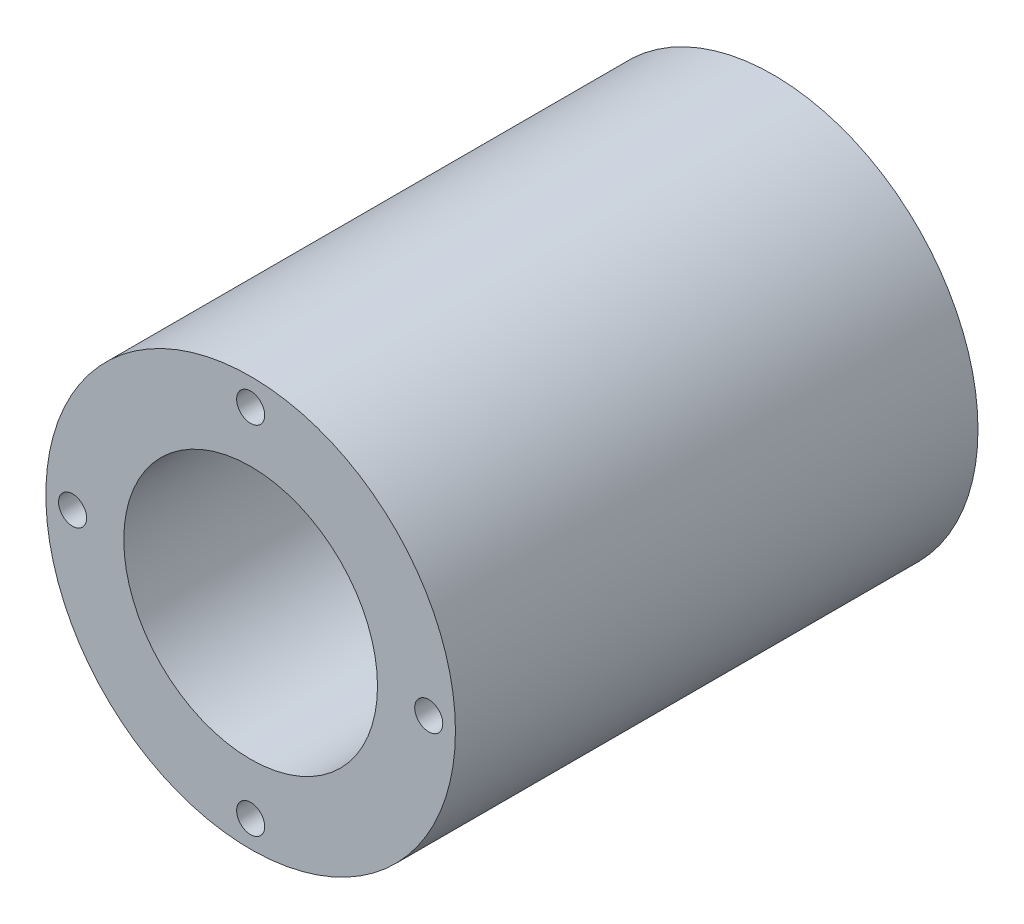
SolidWorks part; units mm, degrees
material "6061-T6 (SS)"
ref_plane "Front Plane" through (0, 0, 0) normal (0, 0, 1) x (1, 0, 0)
ref_plane "Top Plane" through (0, 0, 0) normal (0, 1, 0) x (1, 0, 0)
ref_plane "Right Plane" through (0, 0, 0) normal (1, 0, 0) x (0, 0, -1)
sketch "Sketch Spindle Skeleton" plane through (0, 0, 0) normal (1, 0, 0) x (0, 0, -1)
  line L0 (-95.847, -9.525) -> (-140.95, -9.525)
  line L5 (-1000, 0) -> (49000, 0)
  line L6 (0, -9.525) -> (0, 9.525)
  line L13 (0, 9.525) -> (-45.847, 9.525)
  line L26 (-45.847, 9.525) -> (-45.847, 14)
  line L27 (-45.847, 14) -> (-95.847, 14)
  line L32 (-95.847, 14) -> (-95.847, 9.525)
  line L34 (-160, 7) -> (-160, -7)
  line L36 (-95.847, -9.525) -> (-95.847, -14)
  line L37 (-95.847, -14) -> (-45.847, -14)
  line L38 (-45.847, -14) -> (-45.847, -9.525)
  line L39 (0, -9.525) -> (-45.847, -9.525)
  line L40 (-25.305, 36.5125) -> (-16.305, 36.5125)
  line L41 (-111.341, 22.6187) -> (-95.847, 22.6187)
  line L42 (-111.341, 22.6187) -> (-111.341, -22.6187)
  line L43 (-111.341, -22.6187) -> (-95.847, -22.6187)
  line L44 (-95.847, 22.6187) -> (-95.847, -22.6187)
  line L45 (-111.341, 22.6187) -> (-95.847, -22.6187) construction
  line L46 (-111.341, -22.6187) -> (-95.847, 22.6187) construction
  line L47 (-30.353, 22.6187) -> (-45.847, 22.6187)
  line L48 (-30.353, 22.6187) -> (-30.353, -22.6187)
  line L49 (-30.353, -22.6187) -> (-45.847, -22.6187)
  line L50 (-45.847, 22.6187) -> (-45.847, -22.6187)
  line L51 (-30.353, 22.6187) -> (-45.847, -22.6187) construction
  line L52 (-30.353, -22.6187) -> (-45.847, 22.6187) construction
  line L59 (-16.305, 36.5125) -> (-16.305, -36.5125)
  line L60 (-16.305, -36.5125) -> (-25.305, -36.5125)
  line L61 (-25.305, -22.6187) -> (-27.305, -22.6187)
  line L62 (-27.305, -22.6187) -> (-27.305, -12.5)
  line L63 (-27.305, -12.5) -> (-25.305, -12.5)
  line L64 (-25.305, -12.5) -> (-25.305, 12.5)
  line L65 (-25.305, 12.5) -> (-27.305, 12.5)
  line L66 (-27.305, 12.5) -> (-27.305, 22.6187)
  line L67 (-27.305, 22.6187) -> (-25.305, 22.6187)
  line L68 (-25.305, 22.6187) -> (-25.305, 36.5125)
  line L69 (-25.305, -22.6187) -> (-25.305, -36.5125)
  line L71 (-119.469, 36.5125) -> (-26.305, 36.5125)
  line L72 (-119.469, 36.5125) -> (-119.469, -36.5125)
  line L73 (-119.469, -36.5125) -> (-26.305, -36.5125)
  line L74 (-26.305, 36.5125) -> (-26.305, -36.5125)
  line L75 (-119.469, 36.5125) -> (-26.305, -36.5125) construction
  line L76 (-119.469, -36.5125) -> (-26.305, 36.5125) construction
  line L77 (-140.95, -9.525) -> (-140.95, -7)
  line L78 (-140.95, -7) -> (-160, -7)
  line L79 (-95.847, 9.525) -> (-140.95, 9.525)
  line L80 (-140.95, 7) -> (-160, 7)
  line L81 (-140.95, 9.525) -> (-140.95, 7)
  line L82 (-118.3985, 9.525) -> (-118.3985, -9.525) construction
  line L83 (-22.9235, 9.525) -> (-22.9235, -9.525) construction
  line L96 (-119.469, 36.5125) -> (-134.709, 36.5125)
  line L98 (-119.469, -36.5125) -> (-134.709, -36.5125)
  line L99 (-134.709, 36.5125) -> (-134.709, -36.5125)
  line L110 (-119.469, 36.5125) -> (-119.469, -36.5125)
  point P3 (0, 0)
  point P7 (0, 0)
  point P18 (-103.594, 0)
  point P24 (-38.1, 0)
  point P29 (-72.887, 0)
  point P44 (0, 0)
  point P45 (0, 0)
  point P48 (-16.305, 30.5656)
  point P58 (0, 0)
  point P59 (0, 0)
  point P70 (-134.709, 31.75)
sketch "Sketch1" plane through (0, 0, 0) normal (1, 0, 0) x (0, 0, -1)
  line L0 (-26.305, 36.5125) -> (-26.305, -36.5125) construction
  line L1 (-119.469, -36.5125) -> (-26.305, -36.5125) construction
  line L2 (-119.469, 36.5125) -> (-119.469, -36.5125) construction
  line L3 (-119.469, 36.5125) -> (-26.305, 36.5125) construction
  line L4 (-26.305, 36.5125) -> (-26.305, -36.5125)
  line L5 (-119.469, -36.5125) -> (-26.305, -36.5125)
  line L6 (-119.469, 36.5125) -> (-119.469, -36.5125)
  line L7 (-119.469, 36.5125) -> (-26.305, 36.5125)
  line L9 (-30.353, 22.6187) -> (-45.847, 22.6187) construction
  line L10 (-119.469, 22.6187) -> (-26.305, 22.6187)
  line L15 (-119.469, 0) -> (-26.305, 0) construction
revolve "Revolve1" add sketch "Sketch1" angle 360 about L15
sketch "Back Hole Top Location" plane through (0, 0, 26.305) normal (0, 0, -1) x (-1, 0, 0)
  point P9 (0, 30.5656)
hole_wizard "M6x1.0 Tapped Hole3" positions "Sketch8" profile "Sketch9" tap size "M6x1.0" standard "ANSI Metric"
sketch "Sketch8" plane through (0, 0, 26.305) normal (0, 0, -1) x (-1, 0, 0)
  point P0 (0, 30.5656)
  point P3 (0, 0)
  point P4 (0, 0)
  point P5 (0, 0)
  point P6 (0, 0)
sketch "Sketch9" plane through (0, 30.5656, 26.305) normal (1, 0, 0) x (0, 1, 0)
  line L0 (0, 0) -> (0, 16.5022)
  line L1 (0, 16.5022) -> (2.5, 15)
  line L2 (2.5, 15) -> (2.5, 0)
  line L5 (2.5, 0) -> (0, 0)
  line L10 (0, 16.5022) -> (-2.5, 15) construction
  line L11 (0, -6.35) -> (0, 107.95) construction
  dimension "Tap Drill Dia." = 5
  dimension "Tap Drill Depth" = 15
  dimension "Drill Angle" = 118
pattern_circular "BackFacePattern" count 6 over 360 about axis through (0, 0, 0) along (0, 0, 1) of "M6x1.0 Tapped Hole3"
ref_plane "Midplane" through (0, 0, 72.887) normal (0, 0, -1) x (-1, 0, 0)
sketch "Front Hole Top Location" plane through (0, 0, 119.469) normal (0, 0, 1) x (1, 0, 0)
  point P0 (0, 31.75)
  point P2 (0, 0)
  point P3 (0, 0)
  point P4 (0, 0)
hole_wizard "M6x1.0 Tapped Hole2" positions "Sketch5" profile "Sketch6" tap size "M6x1.0" standard "ANSI Metric"
sketch "Sketch5" plane through (0, 0, 119.469) normal (0, 0, 1) x (1, 0, 0)
  point P0 (0, 31.75)
sketch "Sketch6" plane through (0, 31.75, 119.469) normal (1, 0, 0) x (0, -1, 0)
  line L0 (0, 0) -> (0, 16.5022)
  line L1 (0, 16.5022) -> (2.5, 15)
  line L2 (2.5, 15) -> (2.5, 0)
  line L5 (2.5, 0) -> (0, 0)
  line L10 (0, 16.5022) -> (-2.5, 15) construction
  line L11 (0, -6.35) -> (0, 107.95) construction
  dimension "Tap Drill Dia." = 5
  dimension "Tap Drill Depth" = 15
  dimension "Drill Angle" = 118
pattern_circular "FrontFacePattern" count 4 over 360 about axis through (0, 0, 0) along (0, 0, 1) of "M6x1.0 Tapped Hole2"
sketch "Sketch7" plane through (0, 0, 26.305) normal (0, 0, -1) x (-1, 0, 0)
  circle A0 centre (0, 0) radius 26.9875
  circle A1 centre (0, 0) radius 24.6062
  dimension "D1" = 53.975
  dimension "D2" = 49.2125
extrude "Cut-Extrude1" [suppressed] cut sketch "Sketch7" against normal blind 0.5
